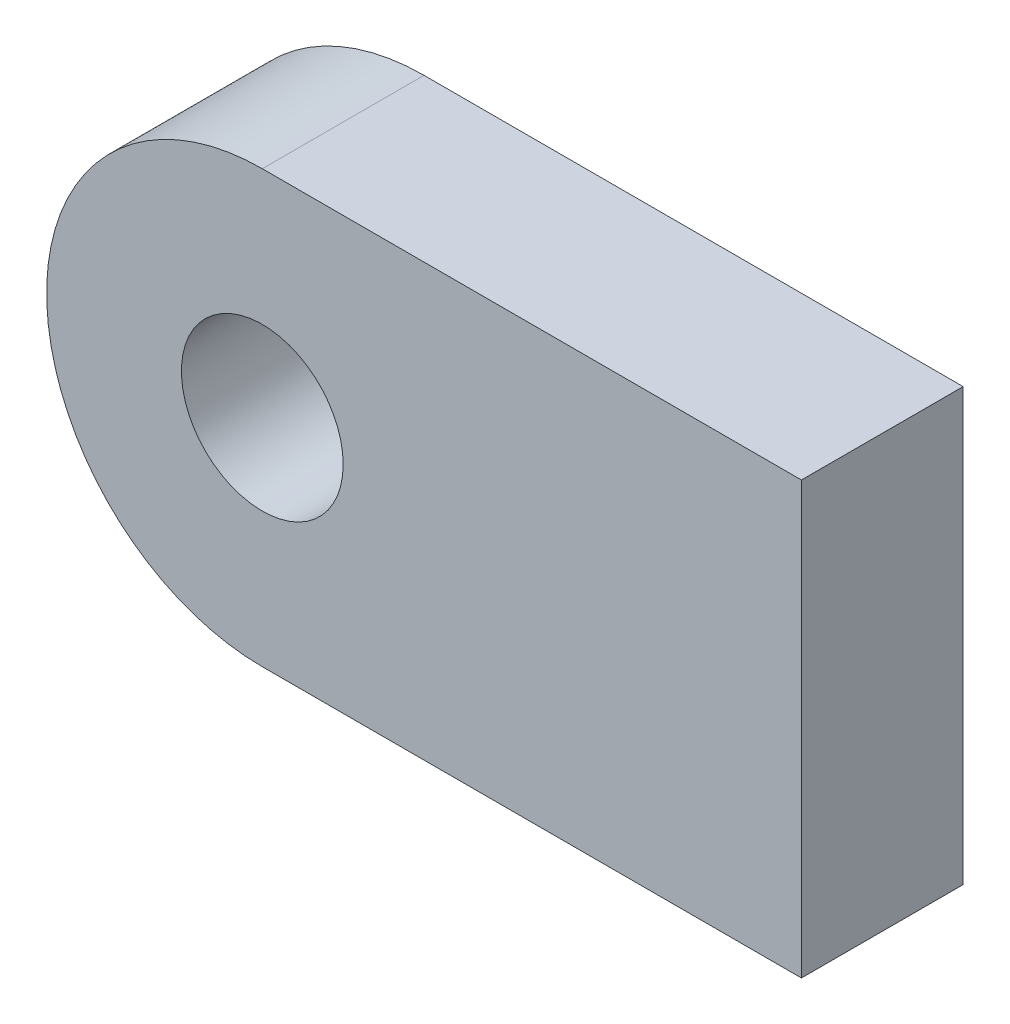
SolidWorks part; units mm, degrees
ref_plane "Front Plane" through (0, 0, 0) normal (0, 0, 1) x (1, 0, 0)
ref_plane "Top Plane" through (0, 0, 0) normal (0, 1, 0) x (1, 0, 0)
ref_plane "Right Plane" through (0, 0, 0) normal (1, 0, 0) x (0, 0, -1)
sketch "Sketch1" plane through (0, 0, 0) normal (0, 0, 1) x (1, 0, 0)
  line L1 (8.5, -1.5) -> (28.5, -1.5)
  line L2 (28.5, -1.5) -> (28.5, 14.5)
  line L3 (28.5, 14.5) -> (8.5, 14.5)
  circle A1 centre (8.5, 6.5) radius 3
  arc A2 (8.5, 14.5) -> (8.5, -1.5) centre (8.5, 6.5) ccw
  point P1 (0, 0)
  point P3 (0, 0)
extrude "Boss-Extrude1" add sketch "Sketch1" along normal blind 6
